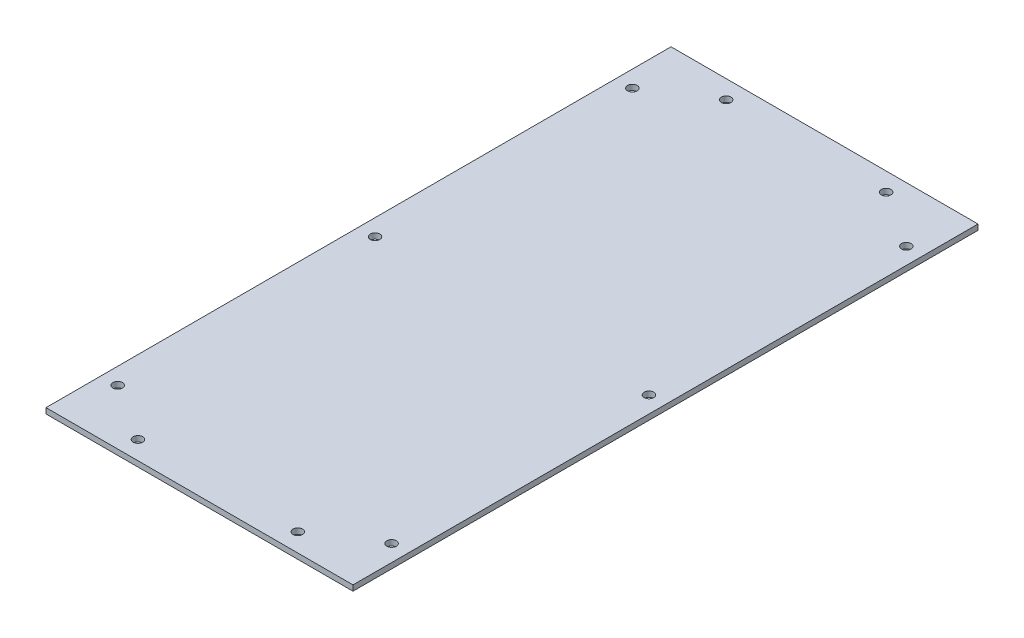
SolidWorks part; units mm, degrees
material "Teak"
ref_plane "Alzado" through (0, 0, 0) normal (0, 0, 1) x (1, 0, 0)
ref_plane "Planta" through (0, 0, 0) normal (0, 1, 0) x (1, 0, 0)
ref_plane "Vista lateral" through (0, 0, 0) normal (1, 0, 0) x (0, 0, -1)
sketch "Croquis1" plane through (0, 0, 0) normal (0, 1, 0) x (1, 0, 0)
  line L0 (-74.5, 170) -> (-74.5, -170) construction
  line L1 (-83.5, 170) -> (83.5, 170)
  line L2 (-83.5, 170) -> (-83.5, -170)
  line L3 (-83.5, -170) -> (83.5, -170)
  line L4 (83.5, 170) -> (83.5, -170)
  line L5 (74.5, 170) -> (74.5, -170) construction
  line L6 (-83.5, 160) -> (83.5, 160) construction
  line L7 (-83.5, -160) -> (83.5, -160) construction
  circle A0 centre (-74.5, 140) radius 2.6
  circle A1 centre (-74.5, 0) radius 2.6
  circle A2 centre (-74.5, -140) radius 2.6
  circle A3 centre (74.5, 140) radius 2.6
  circle A5 centre (74.5, -140) radius 2.6
  circle A6 centre (74.5, 0) radius 2.6
  circle A7 centre (-43.5, 160) radius 2.6
  circle A8 centre (43.5, 160) radius 2.6
  circle A9 centre (-43.5, -160) radius 2.6
  circle A10 centre (43.5, -160) radius 2.6
  point P4 (0, 170)
  point P6 (-83.5, 0)
  dimension "D5" = 5.2
  dimension "D1" = 340
  dimension "D2" = 167
  dimension "D3" = 9
  dimension "D4" = 9
  dimension "D6" = 30
  dimension "D7" = 30
  dimension "D8" = 10
  dimension "D9" = 10
  dimension "D10" = 40
  dimension "D11" = 40
extrude "Saliente-Extruir1" add sketch "Croquis1" along normal blind 3
